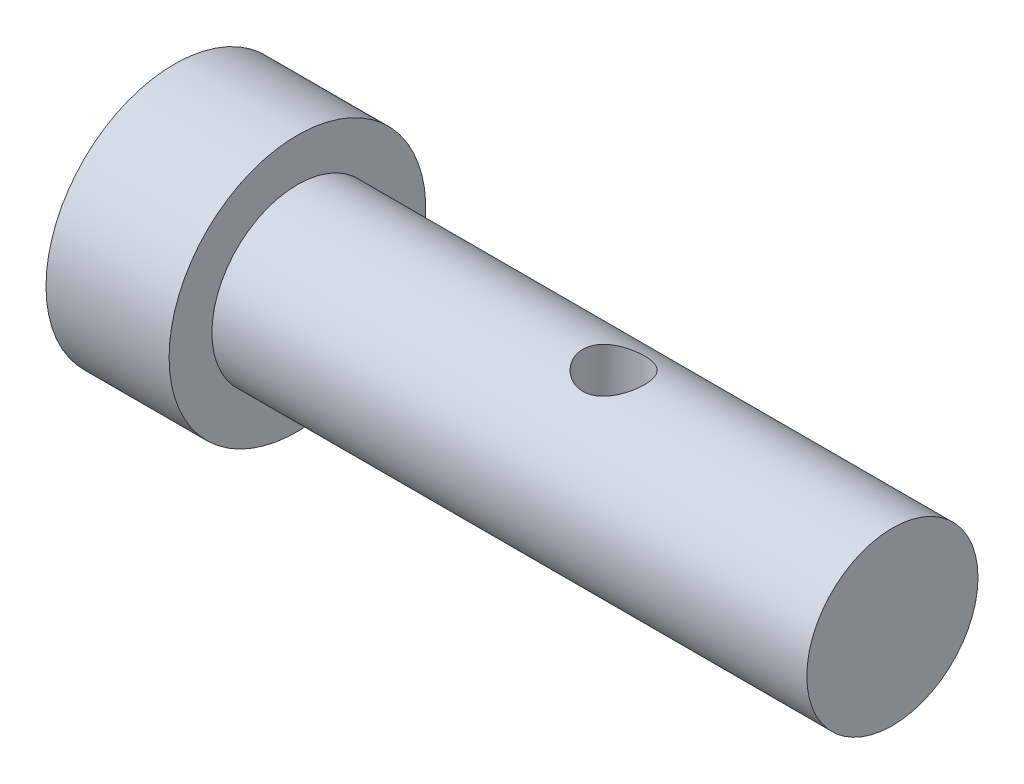
SolidWorks part; units mm, degrees
ref_plane "Front Plane" through (0, 0, 0) normal (0, 0, 1) x (1, 0, 0)
ref_plane "Top Plane" through (0, 0, 0) normal (0, 1, 0) x (1, 0, 0)
ref_plane "Right Plane" through (0, 0, 0) normal (1, 0, 0) x (0, 0, -1)
sketch "Sketch2" plane through (0, 0, 0) normal (0, 1, 0) x (1, 0, 0)
  line L0 (0, 0) -> (0, 8.345)
  line L1 (0, 8.345) -> (-58, 8.345)
  line L2 (-58, 8.345) -> (-58, 12.5175)
  line L3 (-58, 12.5175) -> (-70, 12.5175)
  line L4 (-70, 12.5175) -> (-70, 0)
  line L5 (-70, 0) -> (0, 0)
  dimension "D1" = 8.345
  dimension "D2" = 70
  dimension "D3" = 12.5175
  dimension "D4" = 12
revolve "Revolve1" add sketch "Sketch2" angle 360 about L5
sketch "Sketch4" plane through (0, 0, 0) normal (0, 1, 0) x (1, 0, 0)
  circle A0 centre (-27.181, 0) radius 3
  dimension "D1" = 6
extrude "Cut-Extrude1" cut sketch "Sketch4" along normal through all both and the other way through all
